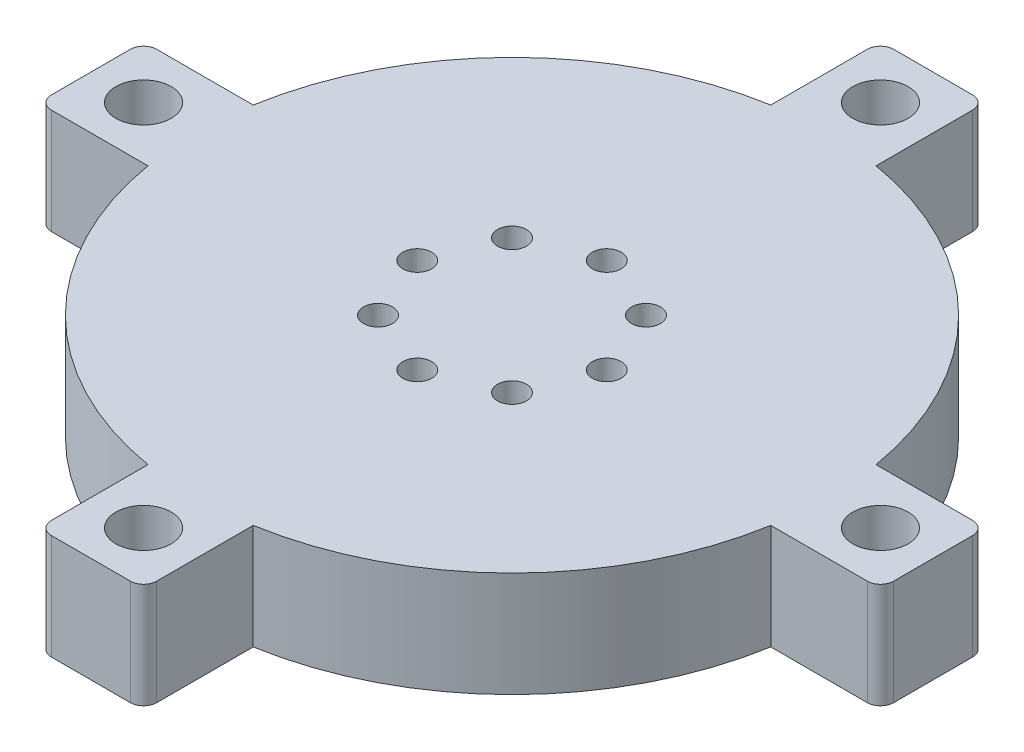
SolidWorks part; units mm, degrees
ref_plane "Front Plane" through (0, 0, 0) normal (0, 0, 1) x (1, 0, 0)
ref_plane "Top Plane" through (0, 0, 0) normal (0, 1, 0) x (1, 0, 0)
ref_plane "Right Plane" through (0, 0, 0) normal (1, 0, 0) x (0, 0, -1)
sketch "Sketch1" plane through (0, 0, 0) normal (0, 1, 0) x (1, 0, 0)
  line L1 (-7.5, 80) -> (7.5, 80)
  line L2 (-10, 77.5) -> (-10, -77.5)
  line L3 (-7.5, -80) -> (7.5, -80)
  line L4 (10, 77.5) -> (10, -77.5)
  line L5 (-10, 80) -> (10, -80) construction
  line L6 (-10, -80) -> (10, 80) construction
  line L7 (-77.5, -10) -> (77.5, -10)
  line L8 (-80, -7.5) -> (-80, 7.5)
  line L9 (-77.5, 10) -> (77.5, 10)
  line L10 (80, -7.5) -> (80, 7.5)
  line L11 (-80, -10) -> (80, 10) construction
  line L12 (-80, 10) -> (80, -10) construction
  circle A0 centre (0, 0) radius 60
  arc A1 (77.5, 10) -> (80, 7.5) centre (77.5, 7.5) cw
  arc A2 (77.5, -10) -> (80, -7.5) centre (77.5, -7.5) ccw
  arc A3 (7.5, -80) -> (10, -77.5) centre (7.5, -77.5) ccw
  arc A4 (-10, -77.5) -> (-7.5, -80) centre (-7.5, -77.5) ccw
  arc A5 (-77.5, -10) -> (-80, -7.5) centre (-77.5, -7.5) cw
  arc A6 (-80, 7.5) -> (-77.5, 10) centre (-77.5, 7.5) cw
  arc A7 (-7.5, 80) -> (-10, 77.5) centre (-7.5, 77.5) ccw
  arc A8 (7.5, 80) -> (10, 77.5) centre (7.5, 77.5) cw
  dimension "D1" = 120
  dimension "D6" = 2.5
  dimension "D2" = 160
  dimension "D3" = 160
  dimension "D4" = 20
  dimension "D5" = 20
extrude "Boss-Extrude1" add sketch "Sketch1" along normal blind 20 contours A6 L8 A5 L7 A0 L9 | L2 A0 L9 | A8 L1 A7 L2 A0 L4 | L4 A0 L2 L9 | L9 A0 L4 | L7 A2 L10 A1 L9 A0 | L7 A0 L9 L4 | L9 L2 L7 L4 | L9 A0 L7 L2 | L7 A0 L2 | L4 A0 L7 | L2 A0 L4 L7 | L2 A4 L3 A3 L4 A0
sketch "Sketch2" plane through (0, 20, 0) normal (0, 1, 0) x (1, 0, 0)
  line L0 (0, 92.9517) -> (0, -90.017) construction
  line L1 (-86.5955, 0) -> (91.0905, 0) construction
  line L2 (80, -7.5) -> (80, 7.5) construction
  line L3 (-7.5, 80) -> (7.5, 80) construction
  line L4 (-80, -7.5) -> (-80, 7.5) construction
  line L5 (-7.5, -80) -> (7.5, -80) construction
  circle A0 centre (0, 0) radius 8.5637 construction
  point P5 (70, 0)
  point P6 (0, 70)
  point P7 (-70, 0)
  point P8 (0, -70)
  point P29 (12.7279, 12.7279)
  point P32 (0, 0)
  dimension "D1" = 10
  dimension "D2" = 10
  dimension "D3" = 10
  dimension "D4" = 10
hole_wizard "CBORE for M5 Hex Head Bolt1" positions "3DSketch1" profile "Sketch3" counterbore size "M5" standard "BSI" end condition through all
sketch3d "3DSketch1"
  point P0 (0, 20, -70)
  point P3 (70, 20, 0)
  point P6 (-70, 20, 0)
  point P9 (0, 20, 70)
sketch "Sketch3" plane through (0, 20, -70) normal (1, 0, 0) x (0, 0, 1)
  line L0 (0, 0) -> (0, 20)
  line L1 (0, 20) -> (2.75, 20)
  line L3 (2.75, 20) -> (2.75, 10)
  line L4 (2.75, 10) -> (5.25, 10)
  line L5 (5.25, 10) -> (5.25, 0)
  line L7 (5.25, 0) -> (0, 0)
  line L11 (0, -6.35) -> (0, 107.95) construction
  dimension "Thru Hole Dia." = 5.5
  dimension "Thru Hole Depth" = 20
  dimension "C'Bore Dia." = 10.5
  dimension "C'Bore Depth" = 10
sketch "Sketch5" plane through (0, 0, 0) normal (0, -1, 0) x (-1, 0, 0)
  line L0 (0, -95.9779) -> (0, 99.6327) construction
  line L1 (96.3978, 0) -> (-99.2128, 0) construction
  point P5 (0, -18)
  point P8 (-12.7279, -12.7279)
  point P9 (-18, 0)
  point P10 (-12.7279, 12.7279)
  point P11 (0, 18)
  point P12 (12.7279, 12.7279)
  point P13 (18, 0)
  point P14 (12.7279, -12.7279)
  dimension "D1" = 18
  dimension "D2" = 8
hole_wizard "CBORE for M5 Hex Head Bolt3" positions "3DSketch3" profile "Sketch6" counterbore size "M5" standard "BSI" end condition through all
sketch3d "3DSketch3"
  point P0 (0, 0, -18)
  point P3 (-12.7279, 0, -12.7279)
  point P6 (-18, 0, 0)
  point P9 (-12.7279, 0, 12.7279)
  point P12 (0, 0, 18)
  point P15 (12.7279, 0, 12.7279)
  point P18 (18, 0, 0)
  point P21 (12.7279, 0, -12.7279)
sketch "Sketch6" plane through (0, 0, -18) normal (1, 0, 0) x (0, 0, -1)
  line L0 (0, 0) -> (0, 20)
  line L1 (0, 20) -> (2.75, 20)
  line L3 (2.75, 20) -> (2.75, 14)
  line L4 (2.75, 14) -> (5.25, 14)
  line L5 (5.25, 14) -> (5.25, 0)
  line L7 (5.25, 0) -> (0, 0)
  line L11 (0, -6.35) -> (0, 107.95) construction
  dimension "Thru Hole Dia." = 5.5
  dimension "Thru Hole Depth" = 20
  dimension "C'Bore Dia." = 10.5
  dimension "C'Bore Depth" = 14
